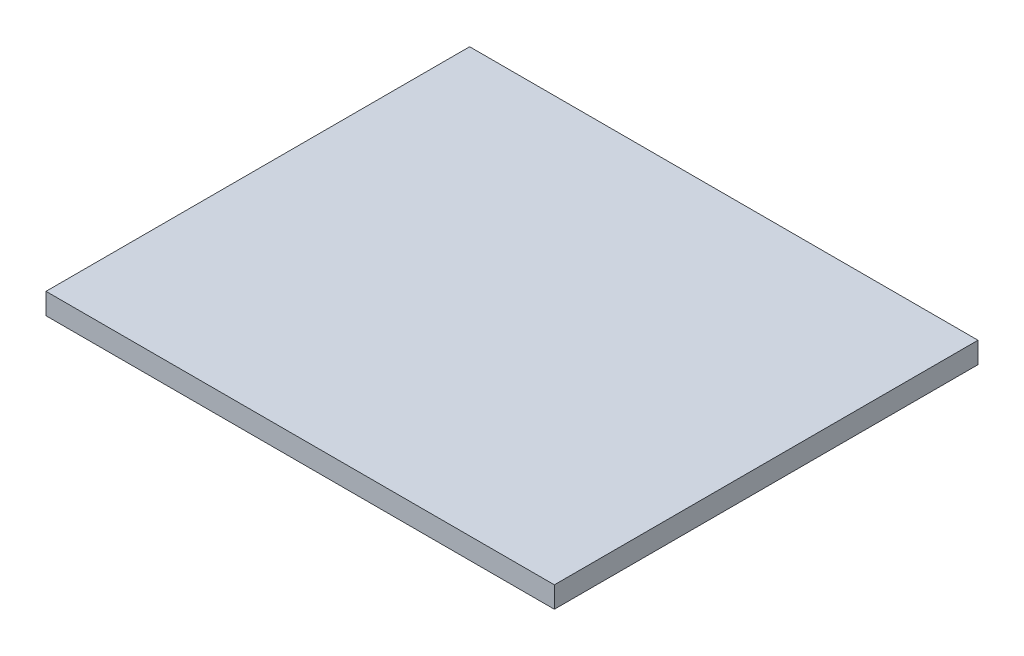
SolidWorks part; units mm, degrees
ref_plane "Front Plane" through (0, 0, 0) normal (0, 0, 1) x (1, 0, 0)
ref_plane "Top Plane" through (0, 0, 0) normal (0, 1, 0) x (1, 0, 0)
ref_plane "Right Plane" through (0, 0, 0) normal (1, 0, 0) x (0, 0, -1)
sketch "Sketch1" plane through (0, 0, 0) normal (0, 1, 0) x (1, 0, 0)
  line L0 (-152.4, 127) -> (152.4, -127) construction
  line L1 (-152.4, 127) -> (152.4, 127)
  line L2 (-152.4, 127) -> (-152.4, -127)
  line L3 (-152.4, -127) -> (152.4, -127)
  line L4 (152.4, 127) -> (152.4, -127)
  dimension "D1" = 254
  dimension "D2" = 304.8
extrude "Boss-Extrude1" add sketch "Sketch1" along normal blind 12.7
